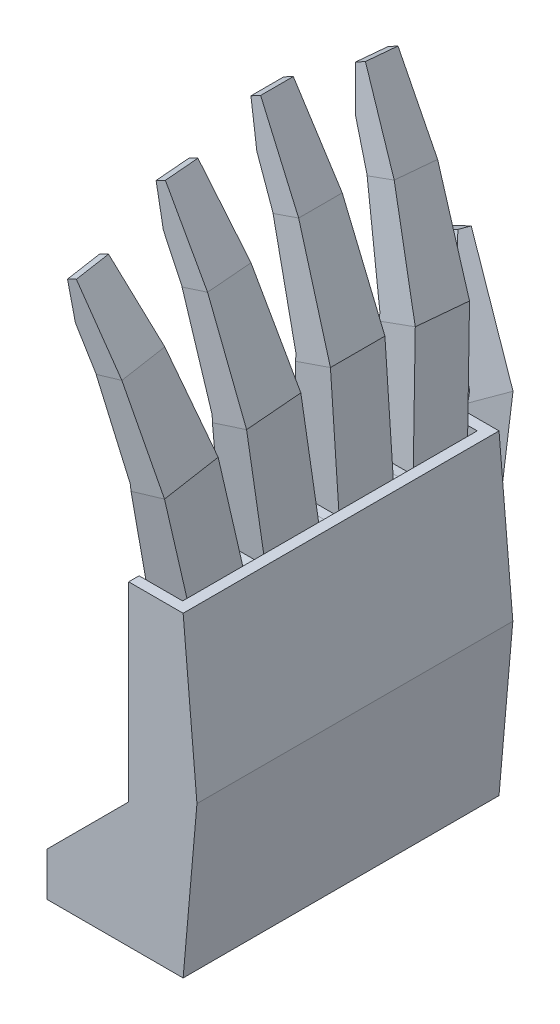
SolidWorks part; units mm, degrees
ref_plane "前视基准面" through (0, 0, 0) normal (0, 0, 1) x (1, 0, 0)
ref_plane "上视基准面" through (0, 0, 0) normal (0, 1, 0) x (1, 0, 0)
ref_plane "右视基准面" through (0, 0, 0) normal (1, 0, 0) x (0, 0, -1)
sketch "草图1" plane through (0, 0, 0) normal (0, 0, 1) x (1, 0, 0)
  line L0 (0, 0) -> (25, 0)
  line L1 (25, 0) -> (27.5372, 29)
  line L2 (27.5372, 29) -> (25, 58)
  line L3 (25, 58) -> (15, 58)
  line L4 (15, 58) -> (15, 23)
  line L5 (15, 23) -> (0, 8)
  line L6 (0, 8) -> (0, 0)
  dimension "D1" = 58
  dimension "D2" = 25
  dimension "D3" = 29
  dimension "D4" = 85
  dimension "D5" = 10
  dimension "D6" = 8
  dimension "D7" = 45
extrude "凸台-拉伸1" add sketch "草图1" along normal mid plane 58
sketch "草图2" plane through (15, 0, 0) normal (-1, 0, 0) x (0, 0, 1)
  line L0 (-27, 58) -> (-27, 55.8147)
  line L1 (29, 58) -> (-29, 58) construction
  line L2 (-27, 55.8147) -> (-13.4518, 57)
  line L3 (-13.4518, 57) -> (0.1482, 57)
  line L4 (0.1482, 57) -> (13.6965, 55.8147)
  line L5 (13.6965, 55.8147) -> (27.0899, 53.4531)
  line L6 (27.0899, 53.4531) -> (27.0899, 58)
  line L7 (27.0899, 58) -> (-27, 58)
  line L8 (-29, 58) -> (-29, 23) construction
  dimension "D1" = 13.6
  dimension "D2" = 13.6
  dimension "D3" = 13.6
  dimension "D4" = 13.6
  dimension "D5" = 5
  dimension "D6" = 5
  dimension "D7" = 5
  dimension "D8" = 2
  dimension "D9" = 1
extrude "切除-拉伸1" cut sketch "草图2" against normal blind 8
ref_plane "基准面1" through (15, 56.4073, -20.2259) normal (0, 0.0872, 0.9962) x (1, 0, 0)
sketch "草图3" plane through (15, 56.4073, -20.2259) normal (0, 0.0872, 0.9962) x (1, 0, 0)
  line L0 (-9.3234, 54.045) -> (-8.1715, 46.661)
  line L1 (0, 0) -> (8, 0)
  line L2 (8, 0) -> (6.4654, 21.9464)
  line L3 (6.4654, 21.9464) -> (-0.046, 40.8568)
  line L4 (-0.046, 40.8568) -> (-7.5576, 54.9839)
  line L5 (-7.5576, 54.9839) -> (-9.3234, 54.045)
  line L6 (-8.1715, 46.661) -> (-4.9176, 39.3526)
  line L7 (-4.9176, 39.3526) -> (0, 21)
  line L8 (0, 21) -> (0, 0)
  dimension "D1" = 22
  dimension "D2" = 20
  dimension "D3" = 16
  dimension "D4" = 15
  dimension "D5" = 9
  dimension "D6" = 2
  dimension "D7" = 4
  dimension "D8" = 4
  dimension "D9" = 4
  dimension "D10" = 21
  dimension "D11" = 19
  dimension "D12" = 8
extrude "凸台-拉伸3" add sketch "草图3" along normal mid plane 10
ref_plane "基准面2" through (15, 57, -6.6518) normal (0, 0, 1) x (1, 0, 0)
sketch "草图4" plane through (15, 57, -6.6518) normal (0, 0, 1) x (1, 0, 0)
  line L0 (0, 0) -> (8, 0)
  line L1 (8, 0) -> (0, 0) construction
  line L2 (8, 0) -> (6.3956, 22.944)
  line L3 (6.3956, 22.944) -> (-0.4413, 42.7999)
  line L4 (-0.4413, 42.7999) -> (-8.4223, 57.81)
  line L5 (-8.4223, 57.81) -> (-10.1882, 56.871)
  line L6 (-10.1882, 56.871) -> (-8.6336, 49.0837)
  line L7 (-5.1764, 41.3185) -> (0, 22)
  line L8 (0, 22) -> (0, 0)
  line L9 (0, 1) -> (0, -34) construction
  line L10 (-8.6336, 49.0837) -> (-5.1764, 41.3185)
  dimension "D1" = 4
  dimension "D2" = 8
  dimension "D3" = 15
  dimension "D4" = 23
  dimension "D5" = 21
  dimension "D6" = 9
  dimension "D7" = 17
  dimension "D8" = 2
  dimension "D9" = 4
  dimension "D10" = 22
  dimension "D11" = 20
  dimension "D12" = 4
  dimension "D13" = 8.5
extrude "凸台-拉伸4" add sketch "草图4" along normal mid plane 10
ref_plane "基准面3" through (15, 56.4073, 6.9224) normal (0, -0.0872, 0.9962) x (1, 0, 0)
sketch "草图5" plane through (15, 56.4073, 6.9224) normal (0, -0.0872, 0.9962) x (1, 0, 0)
  line L0 (0, 0) -> (8, 0)
  line L1 (8, 0) -> (6.4654, 21.9464)
  line L2 (6.4654, 21.9464) -> (-0.046, 40.8568)
  line L3 (-0.046, 40.8568) -> (-7.5576, 54.9839)
  line L4 (-7.5576, 54.9839) -> (-9.3234, 54.045)
  line L5 (-4.9176, 39.3526) -> (-8.1715, 46.661)
  line L6 (-4.9176, 39.3526) -> (0, 21)
  line L7 (0, 21) -> (0, 0)
  line L8 (-8.1715, 46.661) -> (-9.3234, 54.045)
  dimension "D1" = 21
  dimension "D2" = 19
  dimension "D3" = 8
  dimension "D4" = 22
  dimension "D5" = 4
  dimension "D6" = 20
  dimension "D7" = 15
  dimension "D8" = 4
  dimension "D9" = 9
  dimension "D10" = 16
  dimension "D11" = 2
  dimension "D12" = 4
extrude "凸台-拉伸7" add sketch "草图5" along normal mid plane 10
ref_plane "基准面4" through (15, 54.6339, 20.3932) normal (0, -0.1736, 0.9848) x (1, 0, 0)
sketch "草图6" plane through (15, 54.6339, 20.3932) normal (0, -0.1736, 0.9848) x (1, 0, 0)
  line L0 (0, 0) -> (8, 0)
  line L1 (8, 0) -> (6.5351, 20.9488)
  line L2 (6.5351, 20.9488) -> (0.6749, 37.9682)
  line L3 (0.6749, 37.9682) -> (-6.3672, 51.2124)
  line L4 (-6.3672, 51.2124) -> (-8.1331, 50.2735)
  line L5 (-8.1331, 50.2735) -> (-7.4504, 43.2723)
  line L6 (-4.3999, 36.4207) -> (0, 20)
  line L7 (0, 20) -> (0, 0)
  line L9 (-7.4504, 43.2723) -> (-4.3999, 36.4207)
  dimension "D1" = 21
  dimension "D2" = 18
  dimension "D3" = 15
  dimension "D4" = 2
  dimension "D5" = 15
  dimension "D6" = 9
  dimension "D7" = 4
  dimension "D8" = 20
  dimension "D9" = 17
  dimension "D10" = 4
  dimension "D11" = 7.5
  dimension "D12" = 4
extrude "凸台-拉伸8" add sketch "草图6" along normal mid plane 10
sketch "草图9" plane through (43.7864, 15.0195, -1.314) normal (0.9455, 0.3243, -0.0284) x (-0.0277, -0.0068, -0.9996)
  line L0 (16.0191, 67.4434) -> (18.7143, 87.2862)
  line L1 (17.7179, 87.3711) -> (27.6817, 86.5217) construction
  line L2 (18.7143, 87.2862) -> (21.0529, 102.9471)
  line L3 (19.0601, 103.117) -> (29.024, 102.2676) construction
  line L4 (21.0529, 102.9471) -> (27.0312, 102.4375)
  line L5 (27.0312, 102.4375) -> (26.6853, 86.6067)
  line L6 (26.6853, 86.6067) -> (25.983, 66.594)
  line L7 (25.983, 66.594) -> (29.6298, 109.3738)
  line L8 (16.0191, 67.4434) -> (19.6659, 110.2232)
  line L9 (19.6659, 110.2232) -> (29.6298, 109.3738)
  dimension "D1" = 1
  dimension "D2" = 1
  dimension "D3" = 2
  dimension "D4" = 2
extrude "切除-拉伸2" cut sketch "草图9" against normal blind 8
sketch "草图10" plane through (43.737, 15.0599, 0) normal (0.9455, 0.3256, 0) x (0, 0, -1)
  line L0 (1.6518, 68.6228) -> (2.6518, 89.6228)
  line L1 (1.6518, 89.6228) -> (11.6518, 89.6228) construction
  line L2 (2.6518, 89.6228) -> (3.6518, 106.4135)
  line L3 (1.6518, 106.4135) -> (11.6518, 106.4135) construction
  line L4 (3.6518, 106.4135) -> (9.6518, 106.4135)
  line L5 (9.6518, 106.4135) -> (10.6518, 89.6228)
  line L6 (10.6518, 89.6228) -> (11.6518, 68.6228)
  line L7 (11.6518, 68.6228) -> (11.6518, 115.5719)
  line L8 (1.6518, 68.6228) -> (1.6518, 115.5719)
  line L9 (1.6518, 115.5719) -> (11.6518, 115.5719)
  dimension "D1" = 1
  dimension "D2" = 1
  dimension "D3" = 2
  dimension "D4" = 2
extrude "切除-拉伸3" cut sketch "草图10" against normal blind 8
sketch "草图11" plane through (43.4295, 14.8971, 1.3033) normal (0.9455, 0.3243, 0.0284) x (0.0277, 0.0068, -0.9996)
  line L0 (-12.6849, 66.6273) -> (-13.3872, 86.64)
  line L1 (-14.3836, 86.5551) -> (-4.4198, 87.4044) construction
  line L2 (-13.3872, 86.64) -> (-13.7331, 102.4708)
  line L3 (-15.7259, 102.301) -> (-5.762, 103.1503) construction
  line L4 (-13.7331, 102.4708) -> (-7.7548, 102.9805)
  line L5 (-7.7548, 102.9805) -> (-5.4161, 87.3195)
  line L6 (-5.4161, 87.3195) -> (-2.721, 67.4767)
  line L7 (-2.721, 67.4767) -> (-6.5466, 112.3544)
  line L8 (-12.6849, 66.6273) -> (-16.4782, 111.1264)
  line L9 (-16.4782, 111.1264) -> (-6.5466, 112.3544)
  dimension "D1" = 1
  dimension "D2" = 1
  dimension "D3" = 2
  dimension "D4" = 2
extrude "切除-拉伸4" cut sketch "草图11" against normal blind 8
sketch "草图12" plane through (43.3538, 14.7011, 2.5922) normal (0.9455, 0.3206, 0.0565) x (0.0551, 0.0135, -0.9984)
  line L0 (-26.7189, 63.4086) -> (-28.7812, 81.318)
  line L1 (-29.7668, 81.1487) -> (-19.9112, 82.842) construction
  line L2 (-28.7812, 81.318) -> (-30.3043, 96.0888)
  line L3 (-32.2754, 95.7501) -> (-22.4198, 97.4434) construction
  line L4 (-30.3043, 96.0888) -> (-24.3909, 97.1047)
  line L5 (-24.3909, 97.1047) -> (-20.8967, 82.6727)
  line L6 (-20.8967, 82.6727) -> (-16.8633, 65.1019)
  line L7 (-16.8633, 65.1019) -> (-23.9904, 106.5847)
  line L8 (-23.9904, 106.5847) -> (-33.846, 104.8915)
  line L9 (-33.846, 104.8915) -> (-26.7189, 63.4086)
  dimension "D1" = 1
  dimension "D2" = 1
  dimension "D3" = 2
  dimension "D4" = 2
extrude "切除-拉伸5" cut sketch "草图12" against normal blind 8
sketch "草图13" plane through (0, 0, -29) normal (0, 0, -1) x (-1, 0, 0)
  line L0 (-15, 42) -> (-21, 36)
  line L1 (-15, 58) -> (-15, 23) construction
  line L2 (-21, 36) -> (-21, 0)
  line L3 (0, 0) -> (-25, 0) construction
  line L4 (-21, 0) -> (0, 0)
  line L5 (0, 0) -> (0, 27)
  line L6 (0, 27) -> (-15, 42)
  dimension "D1" = 6
  dimension "D2" = 42
  dimension "D3" = 135
  dimension "D4" = 90
extrude "凸台-拉伸9" add sketch "草图13" along normal blind 4 and the other way blind 15
sketch "草图14" plane through (0, 0, 0) normal (0, -1, 0) x (1, 0, 0)
  line L0 (21, -29) -> (3, -33)
  line L1 (21, -33) -> (0, -33) construction
  line L2 (21, -33) -> (21, -29)
  line L3 (3, -33) -> (0, -30)
  line L4 (0, 29) -> (0, -33) construction
  line L5 (0, -30) -> (0, -35.3564)
  line L6 (0, -35.3564) -> (21, -35.3564)
  line L7 (21, -35.3564) -> (21, -33)
  dimension "D1" = 3
  dimension "D2" = 45
extrude "切除-拉伸6" cut sketch "草图14" against normal through all
sketch "草图15" plane through (7.1294, 0, -32.0824) normal (0.2169, 0, -0.9762) x (-0.9762, 0, -0.2169)
  line L0 (4.2301, 30) -> (-6.1622, 36)
  line L1 (4.2301, 30) -> (4.2301, 0) construction
  line L2 (-6.1622, 36) -> (-12.1622, 25.6077)
  line L3 (-12.1622, 25.6077) -> (-1.7699, 19.6077)
  line L4 (-1.7699, 19.6077) -> (4.2301, 30)
  dimension "D1" = 12
  dimension "D2" = 12
  dimension "D4" = 30
ref_plane "基准面5" through (9.584, 5.6683, 2.1298) normal (-0.8454, -0.5, -0.1879) x (-0.4881, 0.866, -0.1085)
sketch "草图17" plane through (9.584, 5.6683, 2.1298) normal (-0.8454, -0.5, -0.1879) x (-0.4881, 0.866, -0.1085)
  line L1 (16.0958, 32.865) -> (28.0958, 32.865) construction
  line L2 (28.0958, 32.865) -> (2.1151, 32.865) construction
  line L3 (28.0958, 32.865) -> (43.6843, 41.865)
  line L4 (43.6843, 41.865) -> (54.5172, 43.7751)
  line L5 (54.5172, 43.7751) -> (63.7821, 47.7445)
  line L6 (63.7821, 47.7445) -> (63.6077, 49.7368)
  line L7 (63.6077, 49.7368) -> (41.6915, 47.8194)
  line L8 (41.6915, 47.8194) -> (21.7527, 38.5218)
  line L9 (21.7527, 38.5218) -> (16.0958, 32.865)
  line L10 (16.0958, 32.865) -> (28.0958, 32.865)
  dimension "D2" = 45
  dimension "D3" = 20
  dimension "D4" = 5
  dimension "D5" = 5
  dimension "D6" = 18
  dimension "D7" = 11
  dimension "D8" = 22
  dimension "D9" = 22
  dimension "D10" = 2
  dimension "D11" = 30
  dimension "D12" = 8
extrude "凸台-拉伸10" add sketch "草图17" against normal blind 12
sketch "草图18" plane through (11.3814, -3.3214, -42.3765) normal (0.2586, -0.0755, -0.963) x (-0.966, -0.0203, -0.2578)
  line L0 (1.6821, 51.2865) -> (14.5122, 69.332)
  line L1 (12.3242, 70.5413) -> (22.8268, 64.7365) construction
  line L2 (14.5122, 69.332) -> (20.6388, 65.9459)
  line L3 (20.6388, 65.9459) -> (12.1847, 45.4818)
  line L4 (12.1847, 45.4818) -> (26.5194, 71.4176)
  line L5 (26.5194, 71.4176) -> (15.3572, 76.0289)
  line L6 (15.3572, 76.0289) -> (1.6821, 51.2865)
  dimension "D1" = 2.5
  dimension "D2" = 2.5
extrude "切除-拉伸7" cut sketch "草图18" against normal blind 10
sketch "草图19" plane through (0, 0, 0) normal (0, -1, 0) x (1, 0, 0)
  line L0 (0, 29) -> (0, -30) construction
  circle A0 centre (9, 0) radius 4
  circle A1 centre (2.2, 0) radius 0.75
  circle A2 centre (9, 6.8) radius 0.75
  circle A4 centre (9, -6.8) radius 0.75
  circle A5 centre (15.8, 0) radius 0.75 [skipped]
  point P16 (9, 0)
  dimension "D1" = 8
  dimension "D3" = 1.5
  dimension "D4" = 6.8
  dimension "D2" = 9
  dimension "D5" = 4
extrude "切除-拉伸8" cut sketch "草图19" against normal up to next
ref_plane "基准面6" through (0, 3, 0) normal (0, -1, 0) x (-1, 0, 0)
sketch "草图20" plane through (0, 3, 0) normal (0, -1, 0) x (-1, 0, 0)
  circle A0 centre (-9, 6.8) radius 1.4596
  circle A1 centre (-2.2, 0) radius 1.5562
  circle A2 centre (-9, -6.8) radius 1.5
  dimension "D1" = 3
extrude "切除-拉伸9" cut sketch "草图20" against normal up to next
